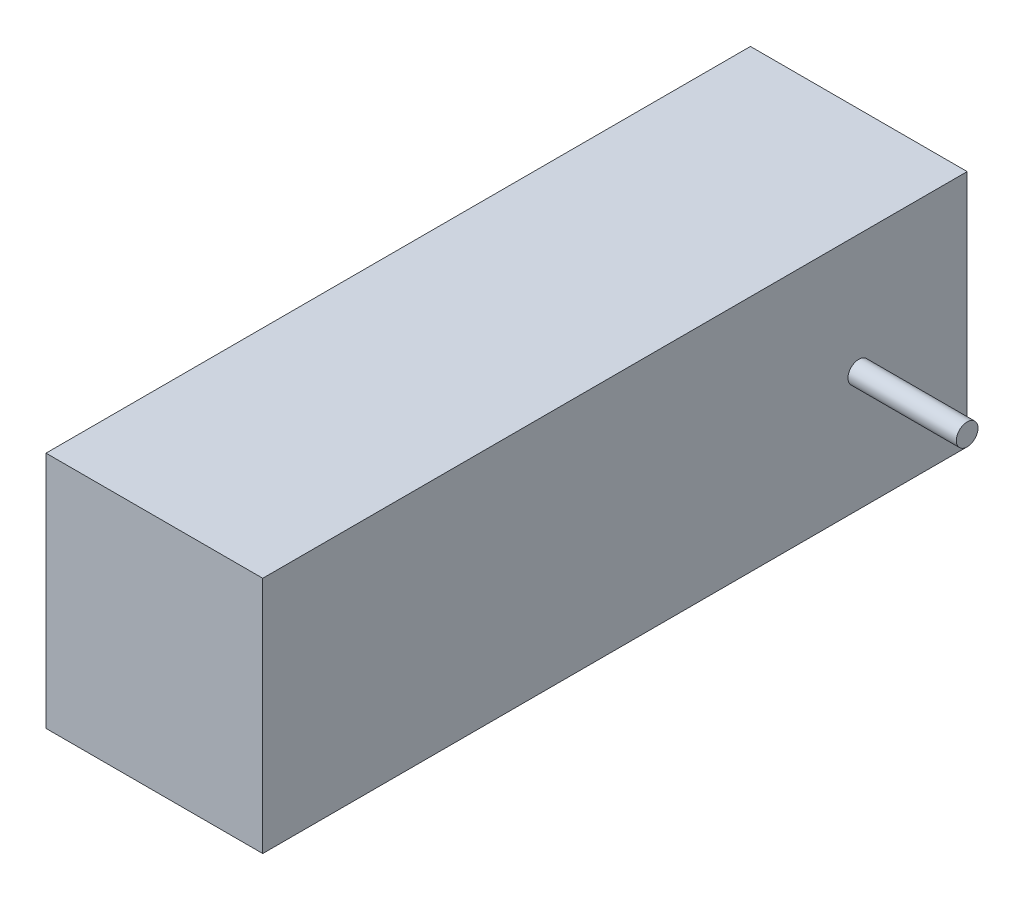
SolidWorks part; units mm, degrees
ref_plane "前基準面" through (0, 0, 0) normal (0, 0, 1) x (1, 0, 0)
ref_plane "上基準面" through (0, 0, 0) normal (0, 1, 0) x (1, 0, 0)
ref_plane "右基準面" through (0, 0, 0) normal (1, 0, 0) x (0, 0, -1)
sketch "草圖1" plane through (0, 0, 0) normal (0, 0, 1) x (1, 0, 0)
  line L1 (10, 11) -> (-10, 11)
  line L2 (10, 11) -> (10, -11)
  line L3 (10, -11) -> (-10, -11)
  line L4 (-10, 11) -> (-10, -11)
  line L5 (10, 11) -> (-10, -11) construction
  line L6 (10, -11) -> (-10, 11) construction
  point P0 (0, 0)
  dimension "D1" = 22
  dimension "D2" = 20
extrude "填料-伸長1" add sketch "草圖1" along normal blind 65
sketch "草圖2" plane through (10, 0, 0) normal (1, 0, 0) x (0, 0, -1)
  line L0 (0, -11) -> (0, 11) construction
  circle A0 centre (-10, 0) radius 1
  dimension "D2" = 2
  dimension "D1" = 10
extrude "填料-伸長2" add sketch "草圖2" along normal blind 10 and the other way blind 28
